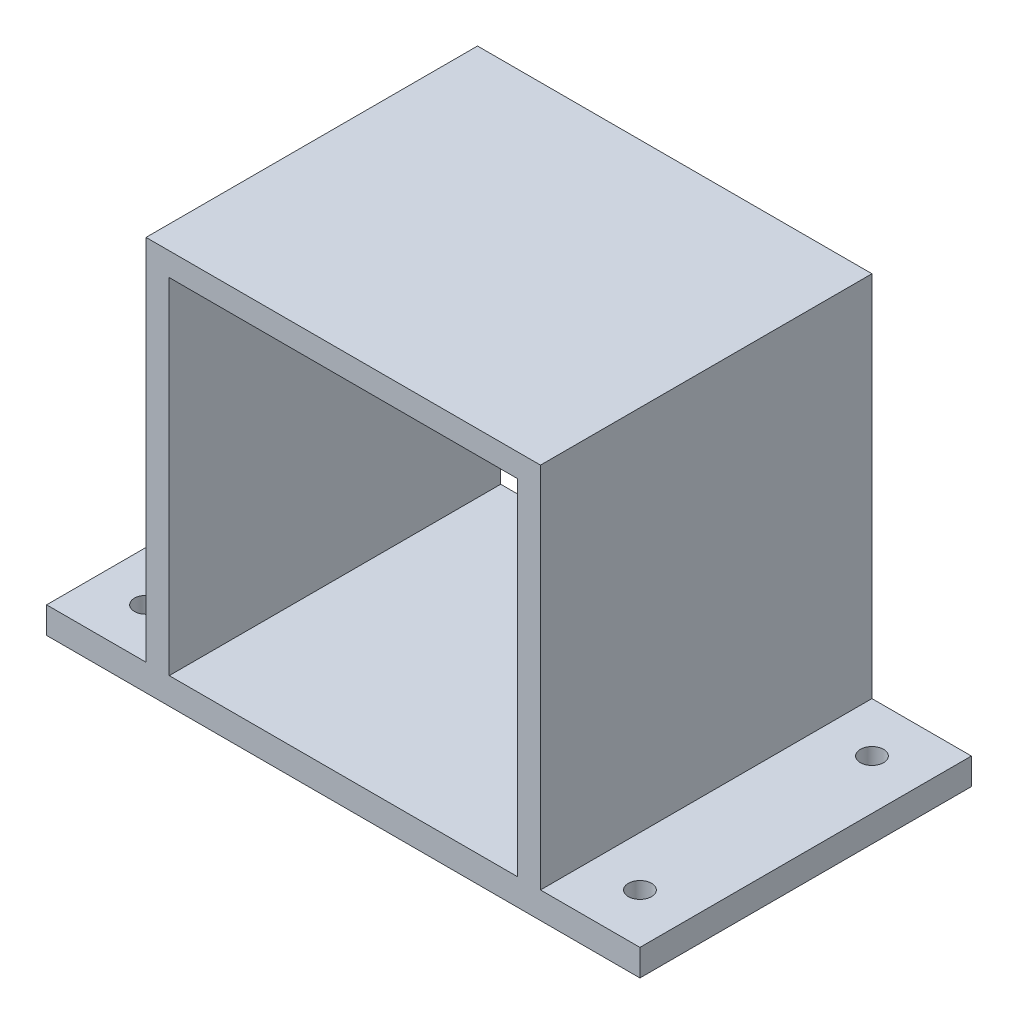
SolidWorks part; units mm, degrees
ref_plane "Front Plane" through (0, 0, 0) normal (0, 0, 1) x (1, 0, 0)
ref_plane "Top Plane" through (0, 0, 0) normal (0, 1, 0) x (1, 0, 0)
ref_plane "Right Plane" through (0, 0, 0) normal (1, 0, 0) x (0, 0, -1)
sketch "Sketch5" plane through (0, 0, 0) normal (0, 0, 1) x (1, 0, 0)
  line L1 (0, 0) -> (52.5, 0)
  line L2 (0, 0) -> (0, 52.5)
  line L3 (0, 52.5) -> (52.5, 52.5)
  line L4 (52.5, 0) -> (52.5, 52.5)
  line L5 (-3.5, 56) -> (56, 56)
  line L6 (-3.5, 56) -> (-3.5, -3.5)
  line L7 (-3.5, -3.5) -> (56, -3.5)
  line L8 (56, 56) -> (56, -3.5)
  dimension "D1" = 52.5
  dimension "D2" = 52.5
  dimension "D3" = 3.5
  dimension "D4" = 3.5
  dimension "D5" = 3.5
  dimension "D6" = 3.5
extrude "Boss-Extrude5" add sketch "Sketch5" along normal blind 50
sketch "Sketch7" plane through (0, -3.5, 0) normal (0, -1, 0) x (1, 0, 0)
  line L0 (-3.5, 50) -> (-18.5, 50)
  line L1 (-18.5, 50) -> (-18.5, 0)
  line L2 (-18.5, 0) -> (71, 0)
  line L3 (71, 0) -> (71, 50)
  line L4 (71, 50) -> (56, 50)
  line L5 (56, 50) -> (56, 0) construction
  line L6 (-3.5, 50) -> (56, 50) construction
  line L7 (26.25, 0) -> (26.25, 50) construction
  line L8 (-3.5, 50) -> (56, 50)
  circle A0 centre (-11, 42.5) radius 1.75
  circle A1 centre (-11, 7.5) radius 1.75
  circle A2 centre (63.5, 7.5) radius 1.75
  circle A3 centre (63.5, 42.5) radius 1.75
  dimension "D3" = 3.5
  dimension "D6" = 3.5
  dimension "D1" = 15
  dimension "D2" = 15
  dimension "D4" = 7.5
  dimension "D5" = 7.5
  dimension "D7" = 7.5
  dimension "D8" = 7.5
extrude "Boss-Extrude7" add sketch "Sketch7" against normal blind 4
